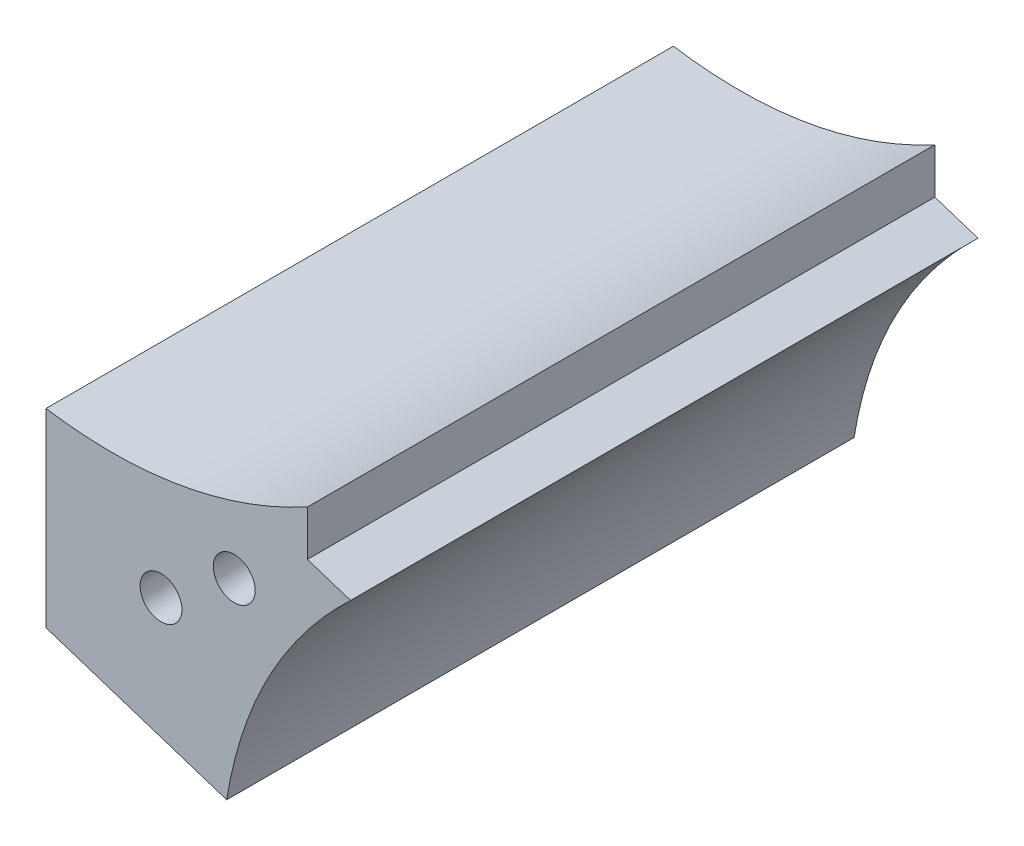
SolidWorks part; units mm, degrees
ref_plane "前视基准面" through (0, 0, 0) normal (0, 0, 1) x (1, 0, 0)
ref_plane "上视基准面" through (0, 0, 0) normal (0, 1, 0) x (1, 0, 0)
ref_plane "右视基准面" through (0, 0, 0) normal (1, 0, 0) x (0, 0, -1)
sketch "草图1" plane through (0, 0, 0) normal (0, 0, 1) x (1, 0, 0)
  line L0 (10.1557, 10.2844) -> (10.1557, 14.6208)
  line L1 (-14.8443, 10.2844) -> (-14.8443, -7.8792)
  line L2 (-14.8443, -7.8792) -> (2.4303, -13.492)
  line L3 (14.2799, 8.9443) -> (10.1557, 10.2844)
  circle A0 centre (-3.8443, 0.1128) radius 2
  circle A1 centre (3.1557, 5.1986) radius 2
  parabola Q0 (10.1557, 14.6208) -> (-14.8443, 10.2844) focus (-5.2941, 28.8715) apex (-2.1666, 10.3139)
  parabola Q1 (2.4303, -13.492) -> (14.2799, 8.9443) focus (23.0588, -10.153) apex (6.376, -1.4439)
extrude "凸台-拉伸1" add sketch "草图1" along normal blind 60
sketch "草图2" plane through (0, 0, 0) normal (0, 0, -1) x (-1, 0, 0)
  line L0 (-3.1557, 5.1986) -> (3.8443, 0.1128) construction
  line L1 (-0.8046, 8.4346) -> (6.1954, 3.3488)
  line L2 (-5.5069, 1.9625) -> (1.4931, -3.1233)
  arc A0 (-0.8046, 8.4346) -> (-5.5069, 1.9625) centre (-3.1557, 5.1986) ccw
  arc A1 (1.4931, -3.1233) -> (6.1954, 3.3488) centre (3.8443, 0.1128) ccw
  point P4 (0.3443, 2.6557)
  dimension "D1" = 4
extrude "切除-拉伸1" cut sketch "草图2" against normal blind 55
